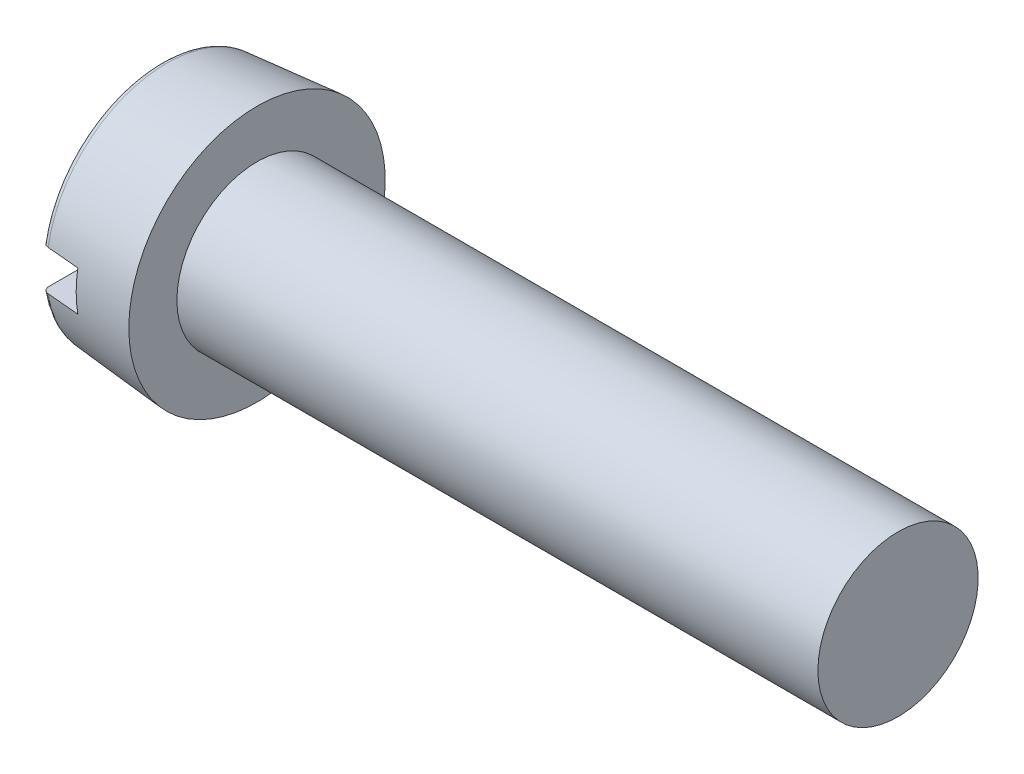
SolidWorks part; units mm, degrees
ref_plane "Plane1" through (0, 0, 0) normal (0, 0, 1) x (1, 0, 0)
ref_plane "Plane2" through (0, 0, 0) normal (0, 1, 0) x (1, 0, 0)
ref_plane "Plane3" through (0, 0, 0) normal (1, 0, 0) x (0, 0, -1)
sketch "BodySke" plane through (0, 0, 0) normal (0, 0, 1) x (1, 0, 0)
  line L0 (6, 5) -> (6, 8)
  line L1 (0, 0) -> (0, 7.4751)
  line L2 (-25.4, 0) -> (127, 0) construction
  line L3 (46, 0) -> (0, 0)
  line L4 (6, 5) -> (46, 5)
  line L5 (46, 5) -> (46, 0)
  line L6 (0, 7.4751) -> (6, 8)
  line L9 (7.5, 6.5875) -> (7.5, -2.9375) construction
  line L10 (6, 6.35) -> (6, -3.175) construction
  dimension "Length" = 40
  dimension "Head_ht" = 6
  dimension "Advance" = 1.5
  dimension "Thread_nom" = 40
  dimension "Head_dia" = 16
  dimension "Head_side_angle" = 5
  dimension "Diameter" = 10
revolve "Base-Revolve" add sketch "BodySke"
cosmetic thread "ThreadCosmetic" [suppressed]
fillet "Fillet1" [suppressed] radius 0.4
fillet "Fillet2" radius 0.4 1 edges at (0, 0, 7.4751)
sketch "Sketch2" plane through (0, 0, 0) normal (1, 0, 0) x (0, 0, -1)
  line L0 (8, -1.25) -> (-8, -1.25)
  line L1 (8, -1.25) -> (8, 1.25)
  line L2 (-8, 1.25) -> (8, 1.25)
  line L3 (-8, 1.25) -> (-8, -1.25)
  dimension "D1" = 16
  dimension "Slot_width" = 2.5
  dimension "D2" = 8
  dimension "D3" = 1.25
extrude "Slot" cut sketch "Sketch2" along normal blind 2.4
sketch "ThdSchSke" plane through (0, 0, 0) normal (0, 0, 1) x (1, 0, 0)
  line L0 (9, -4.1885) -> (8.4318, -5)
  line L1 (9, -4.1885) -> (9.5682, -5)
  line L2 (9.5682, -5) -> (9.5682, -6.25)
  line L3 (-3.175, 0) -> (5.1513, 0) construction
  line L5 (9.5682, -6.25) -> (8.4318, -6.25)
  line L6 (8.4318, -6.25) -> (8.4318, -5)
  dimension "Diameter" = 10
  dimension "SideAngle" = 55
  dimension "VeeAngle" = 70
  dimension "Thread_minor" = 8.377
  dimension "Overcut" = 12.5
  dimension "Start" = 9
revolve "ThreadSchematic" [suppressed] cut sketch "ThdSchSke" angle 360 about L3
pattern_linear "ThdSchPat" [suppressed]
equation "\"D1@Sketch2\" = \"Head_dia@BodySke\""
equation "\"D2@Sketch2\" = \"D1@Sketch2\" / 2"
equation "\"D3@Sketch2\" = \"Slot_width@Sketch2\" / 2"
equation "\"Thread_length@ThreadCosmetic\" = ((sgn( (\"Length@BodySke\" - \"Advance@BodySke\" * 2.0 ) - \"Thread_nom@BodySke\" )-1)*( (\"Length@BodySke\" - \"Advance@BodySke\"  * 2.0) - \"Thread_nom@BodySke\" ))/-2+ \"Thread_nom@BodySke\""
equation "\"Thread_minor@ThdSchSke\" = \"Thread_minor@ThreadCosmetic\""
equation "\"Diameter@ThdSchSke\" = \"Diameter@BodySke\""
equation "\"Overcut@ThdSchSke\" = \"Diameter@BodySke\" * 1.25"
equation "\"Start@ThdSchSke\" = \"Head_ht@BodySke\" + \"Length@BodySke\" - \"Thread_length@ThreadCosmetic\"  '---Non-countersunk---"
equation "\"Num_threads@ThdSchPat\" = int( \"Thread_length@ThreadCosmetic\" / \"Advance@BodySke\" + 0.999 )  + 1"
equation "\"Advance@ThdSchPat\" = \"Thread_length@ThreadCosmetic\" /  (\"Num_threads@ThdSchPat\" - 1) 'relax it"
